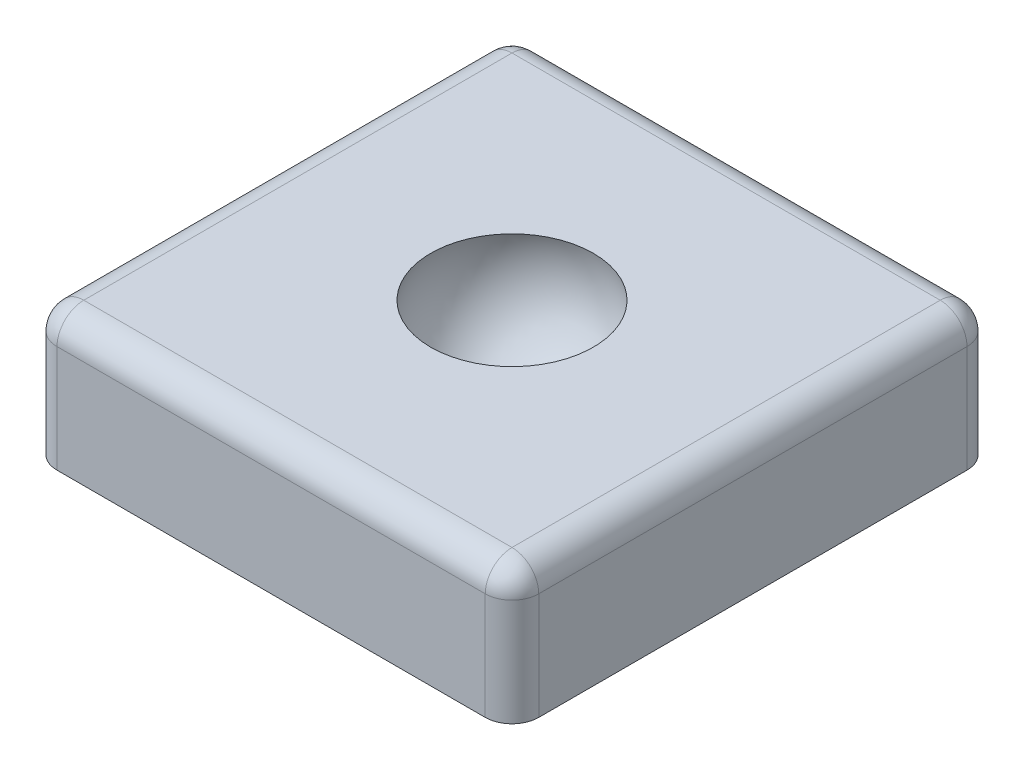
SolidWorks part; units mm, degrees
ref_plane "Спереди" through (0, 0, 0) normal (0, 0, 1) x (1, 0, 0)
ref_plane "Сверху" through (0, 0, 0) normal (0, 1, 0) x (1, 0, 0)
ref_plane "Справа" through (0, 0, 0) normal (1, 0, 0) x (0, 0, -1)
sketch "Эскиз1" plane through (0, 0, 0) normal (0, 1, 0) x (1, 0, 0)
  line L1 (-18, -18) -> (18, -18)
  line L2 (-18, -18) -> (-18, 18)
  line L3 (-18, 18) -> (18, 18)
  line L4 (18, -18) -> (18, 18)
  line L5 (0, 18) -> (0, -18) construction
  line L6 (-18, 0) -> (18, 0) construction
  point P0 (0, 0)
  dimension "D1" = 36
  dimension "D2" = 36
extrude "Бобышка-Вытянуть1" add sketch "Эскиз1" along normal blind 10
ref_plane "Плоскость4" through (0, 8, 0) normal (0, 1, 0) x (1, 0, 0)
sketch "Эскиз4" plane through (0, 8, 0) normal (0, 1, 0) x (1, 0, 0)
  line L0 (-23.5139, 0) -> (32.0068, 0) construction
  line L1 (-6.4, 0) -> (6.4, 0)
  arc A0 (-6.4, 0) -> (6.4, 0) centre (0, 0) cw
  point P5 (0, 0)
  point P7 (0, 0)
  dimension "D1" = 12.8
revolve "Вырез-Повернуть2" cut sketch "Эскиз4" angle 360 about L0
fillet "Скругление1" [suppressed] radius 0.5
fillet "Скругление2" radius 2 8 edges at (0, 10, -18) (18, 10, 0) (0, 10, 18) (-18, 10, 0) (-18, 5, -18) (-18, 5, 18) (18, 5, -18) (18, 5, 18)
